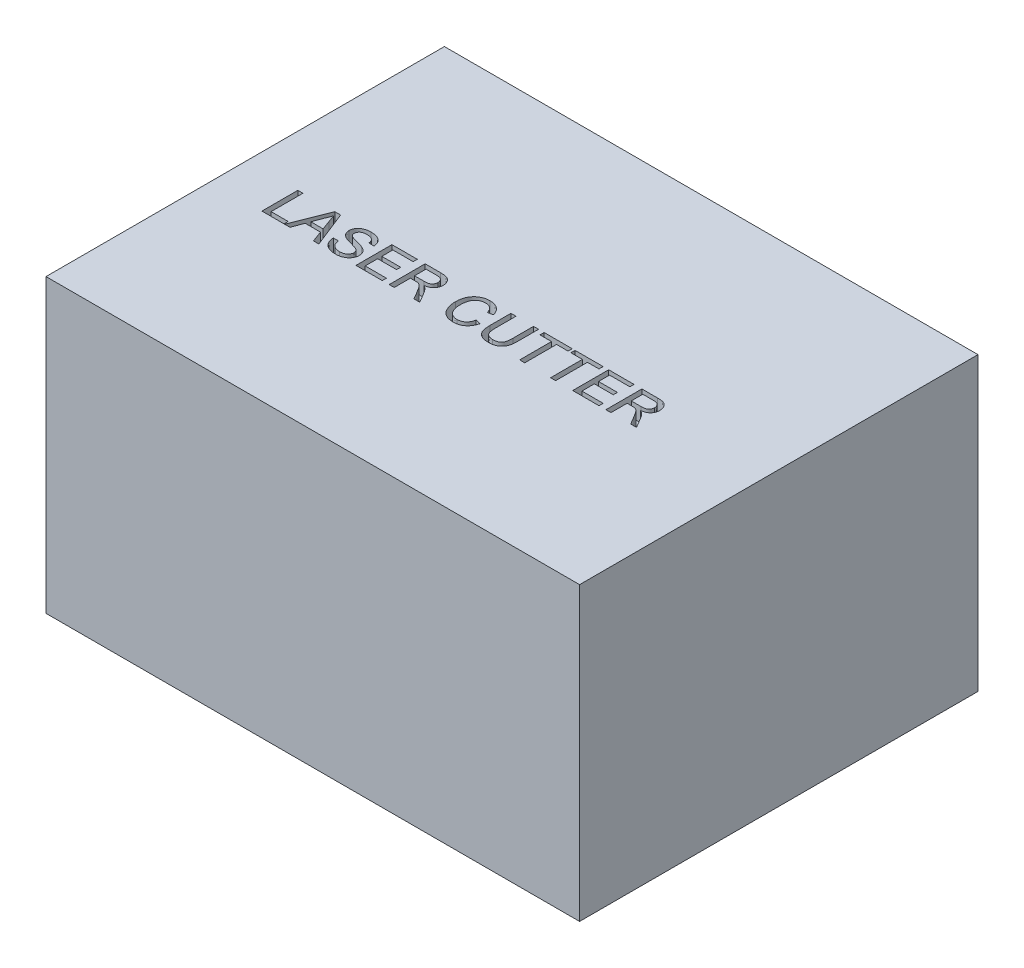
SolidWorks part; units mm, degrees
ref_plane "Front" through (0, 0, 0) normal (0, 0, 1) x (1, 0, 0)
ref_plane "Top" through (0, 0, 0) normal (0, 1, 0) x (1, 0, 0)
ref_plane "Right" through (0, 0, 0) normal (1, 0, 0) x (0, 0, -1)
sketch "Sketch1" plane through (0, 0, 0) normal (0, 1, 0) x (1, 0, 0)
  line L1 (0, 0) -> (1905, 0)
  line L2 (0, 0) -> (0, 1422.4)
  line L3 (0, 1422.4) -> (1905, 1422.4)
  line L4 (1905, 0) -> (1905, 1422.4)
  dimension "D1" = 1905
  dimension "D2" = 1422.4
extrude "Boss-Extrude1" add sketch "Sketch1" along normal blind 1041.4
sketch "Sketch2" plane through (0, 1041.4, 0) normal (0, 1, 0) x (1, 0, 0)
  line L0 (168.0802, 587.8692) -> (1727.8514, 587.8692) construction
  text T0 "LASER CUTTER" font "Arial" height in points 500
extrude "Cut-Extrude1" cut sketch "Sketch2" against normal blind 50.8
